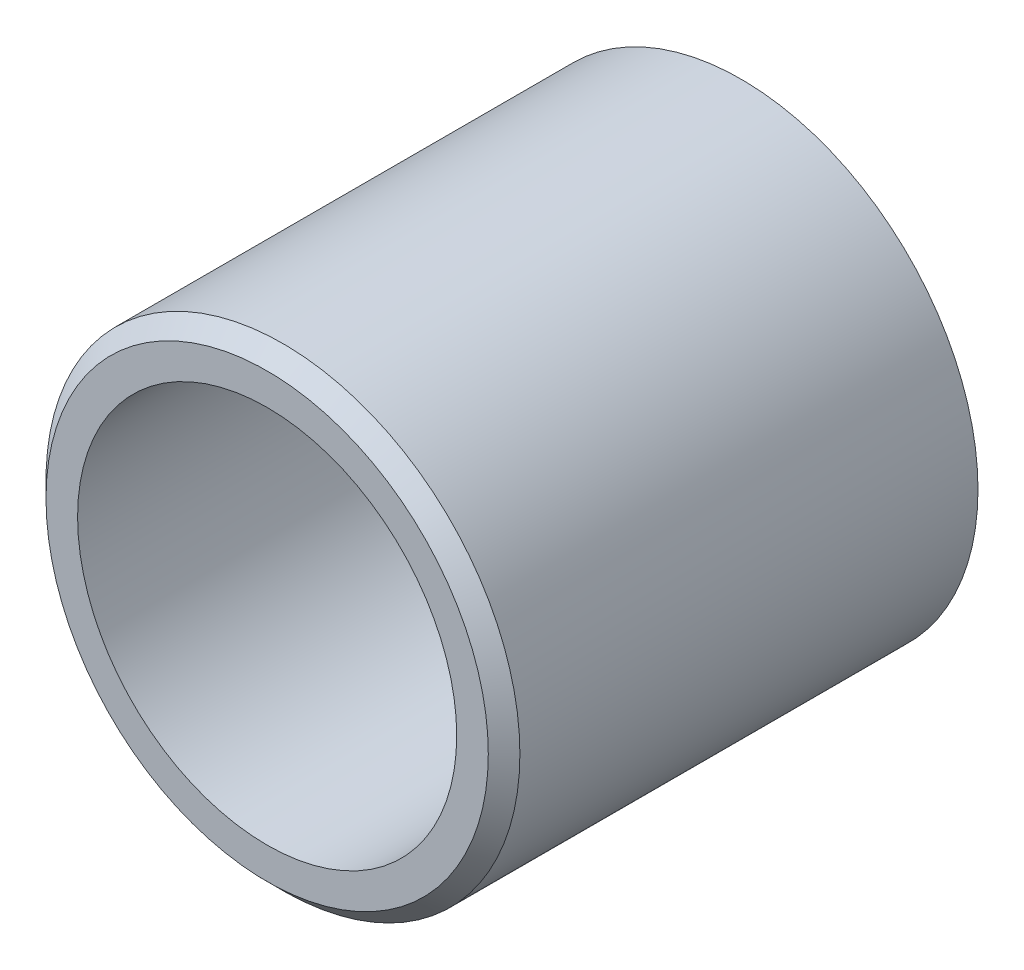
SolidWorks part; units mm, degrees
ref_plane "Front Plane" through (0, 0, 0) normal (0, 0, 1) x (1, 0, 0)
ref_plane "Top Plane" through (0, 0, 0) normal (0, 1, 0) x (1, 0, 0)
ref_plane "Right Plane" through (0, 0, 0) normal (1, 0, 0) x (0, 0, -1)
sketch "Sketch1" plane through (0, 0, 0) normal (0, 0, 1) x (1, 0, 0)
  circle A0 centre (0, 0) radius 7.5
  circle A1 centre (0, 0) radius 6
  dimension "D1" = 15
  dimension "D2" = 12
extrude "Boss-Extrude1" add sketch "Sketch1" along normal blind 15
chamfer "Chamfer1" distance 0.5 angle 45 1 edges at (7.5, 0, 15)
scale "Scale1" scale about centroid uniform scaling yes scale factor 0.317565
